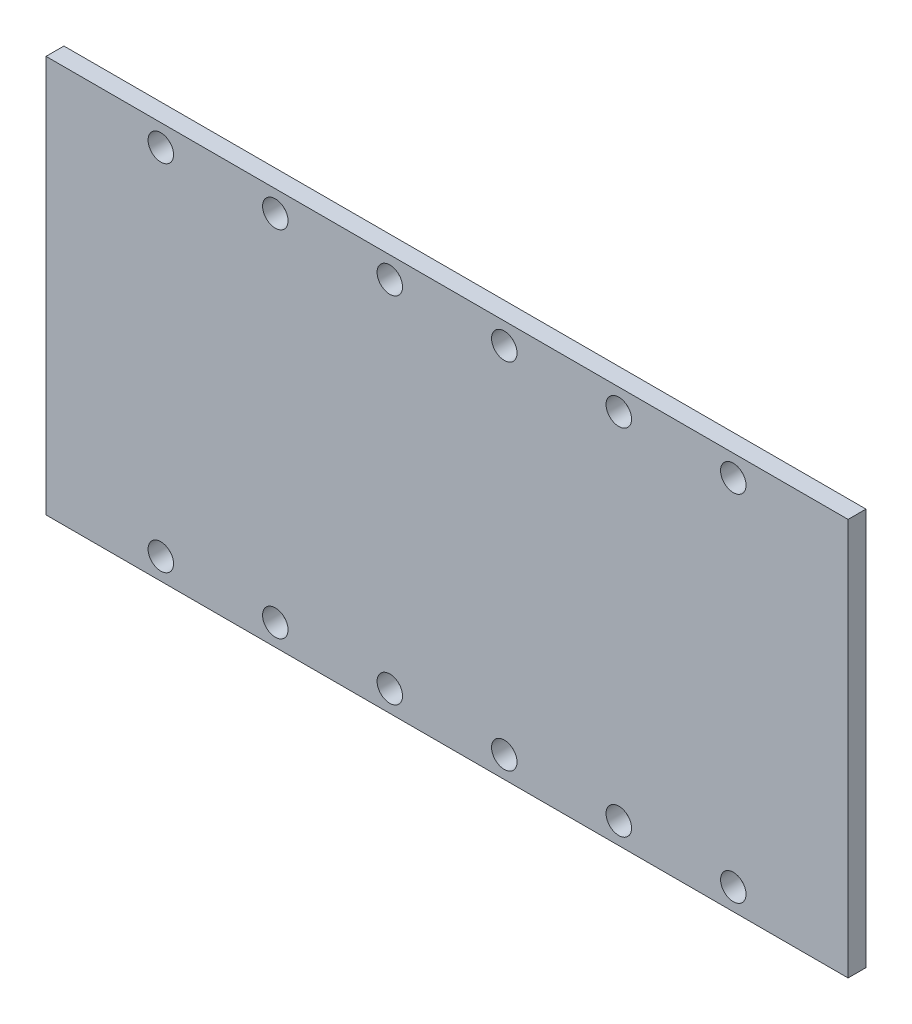
SolidWorks part; units mm, degrees
material "A-Glass Fiber"
ref_plane "Front Plane" through (0, 0, 0) normal (0, 0, 1) x (1, 0, 0)
ref_plane "Top Plane" through (0, 0, 0) normal (0, 1, 0) x (1, 0, 0)
ref_plane "Right Plane" through (0, 0, 0) normal (1, 0, 0) x (0, 0, -1)
sketch "Sketch1" plane through (0, 0, 0) normal (0, 0, 1) x (1, 0, 0)
  line L1 (-35.5854, -17.6212) -> (35.5854, -17.6212)
  line L2 (-35.5854, -17.6212) -> (-35.5854, 17.6212)
  line L3 (-35.5854, 17.6212) -> (35.5854, 17.6212)
  line L4 (35.5854, -17.6212) -> (35.5854, 17.6212)
  line L5 (-35.5854, -17.6212) -> (35.5854, 17.6212) construction
  line L6 (-35.5854, 17.6212) -> (35.5854, -17.6212) construction
  point P0 (0, 0)
  dimension "D1" = 35.2425
  dimension "D2" = 71.1708
extrude "Boss-Extrude1" add sketch "Sketch1" along normal blind 1.5875
sketch "Sketch2" plane through (0, 0, 1.5875) normal (0, 0, 1) x (1, 0, 0)
  line L0 (-35.5854, 15.7163) -> (-25.4, 15.7163) construction
  line L1 (-35.5854, 17.6212) -> (-35.5854, -17.6212) construction
  line L2 (35.5854, 17.6212) -> (-35.5854, 17.6212) construction
  line L3 (0, -0.8731) -> (0, 0.8731) construction
  dimension "D1" = 25.4
  dimension "D2" = 1.905
hole_wizard "#2 Clearance Hole1" positions "Sketch4" profile "Sketch3" hole size "#2" standard "Ansi Inch"
sketch "Sketch4" plane through (0, 0, 1.5875) normal (0, 0, 1) x (1, 0, 0)
  point P1 (-25.4, 15.7163)
sketch "Sketch3" plane through (-25.4, 15.7163, 1.5875) normal (1, 0, 0) x (0, -1, 0)
  line L0 (0, 0) -> (0, 3.8542)
  line L1 (0, 3.8542) -> (1.1303, 3.175)
  line L2 (1.1303, 3.175) -> (1.1303, 0)
  line L5 (1.1303, 0) -> (0, 0)
  line L10 (0, 3.8542) -> (-1.1303, 3.175) construction
  line L11 (0, -6.35) -> (0, 107.95) construction
  dimension "Hole Dia." = 2.2606
  dimension "Hole Depth" = 3.175
  dimension "Drill Angle" = 118
pattern_linear "LPattern1" count 6 spacing 10.16 along (1, 0, 0) of "#2 Clearance Hole1"
mirror "Mirror1" about plane through (0, 0, 0) normal (0, 1, 0) of "LPattern1", "#2 Clearance Hole1"
